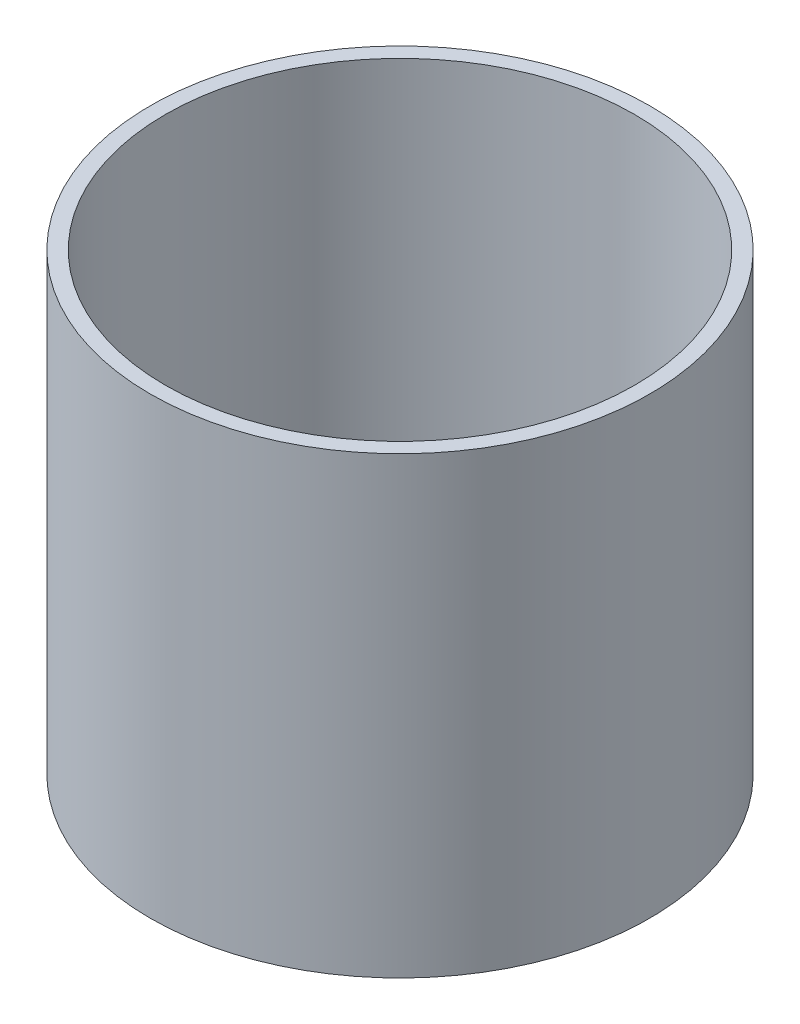
SolidWorks part; units mm, degrees
ref_plane "Front Plane" through (0, 0, 0) normal (0, 0, 1) x (1, 0, 0)
ref_plane "Top Plane" through (0, 0, 0) normal (0, 1, 0) x (1, 0, 0)
ref_plane "Right Plane" through (0, 0, 0) normal (1, 0, 0) x (0, 0, -1)
sketch "Sketch1" plane through (0, 0, 0) normal (0, 1, 0) x (1, 0, 0)
  circle A0 centre (0, 0) radius 31
  circle A1 centre (0, 0) radius 33
  dimension "D1" = 62
  dimension "D2" = 66
extrude "Boss-Extrude1" add sketch "Sketch1" along normal blind 60
